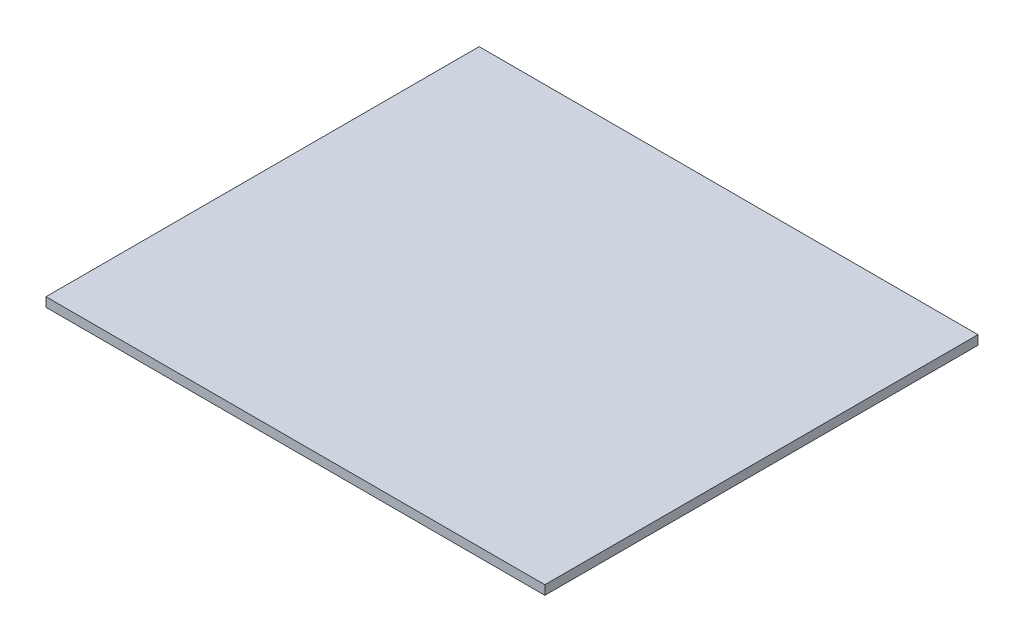
SolidWorks part; units mm, degrees
material "Pine"
ref_plane "Front Plane" through (0, 0, 0) normal (0, 0, 1) x (1, 0, 0)
ref_plane "Top Plane" through (0, 0, 0) normal (0, 1, 0) x (1, 0, 0)
ref_plane "Right Plane" through (0, 0, 0) normal (1, 0, 0) x (0, 0, -1)
sketch "Sketch1" plane through (0, 0, 0) normal (0, 1, 0) x (1, 0, 0)
  line L1 (-515.874, 447.929) -> (515.874, 447.929)
  line L2 (-515.874, 447.929) -> (-515.874, -447.929)
  line L3 (-515.874, -447.929) -> (515.874, -447.929)
  line L4 (515.874, 447.929) -> (515.874, -447.929)
  line L5 (-515.874, 447.929) -> (515.874, -447.929) construction
  line L6 (-515.874, -447.929) -> (515.874, 447.929) construction
  point P0 (0, 0)
  dimension "D1" = 895.858
  dimension "D2" = 1031.748
extrude "Boss-Extrude1" add sketch "Sketch1" along normal blind 19.05
